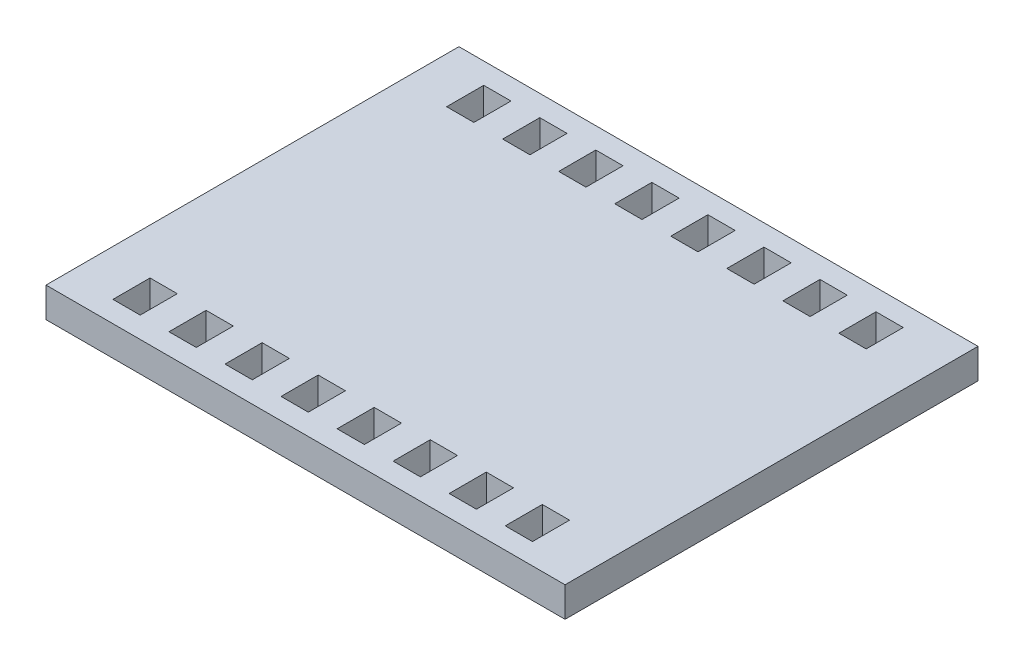
SolidWorks part; units mm, degrees
ref_plane "Front Plane" through (0, 0, 0) normal (0, 0, 1) x (1, 0, 0)
ref_plane "Top Plane" through (0, 0, 0) normal (0, 1, 0) x (1, 0, 0)
ref_plane "Right Plane" through (0, 0, 0) normal (1, 0, 0) x (0, 0, -1)
sketch "Sketch1" plane through (0, 0, 0) normal (0, 1, 0) x (1, 0, 0)
  line L0 (113.6667, 269.5) -> (568.3333, 269.5) construction
  line L1 (8.6379, 33.2139) -> (8.6379, 30.0697)
  line L2 (3.8881, 33.2139) -> (6.1977, 33.2139)
  line L3 (3.8881, 33.2139) -> (3.8881, 30.0697)
  line L4 (3.8881, 30.0697) -> (6.1977, 30.0697)
  line L5 (6.1977, 33.2139) -> (6.1977, 30.0697)
  line L6 (0, 35) -> (43.9961, 35)
  line L7 (0, 35) -> (0, 0)
  line L8 (0, 0) -> (43.9961, 0)
  line L9 (43.9961, 35) -> (43.9961, 0)
  line L10 (8.6379, 33.2139) -> (10.9475, 33.2139)
  line L11 (10.9475, 33.2139) -> (10.9475, 30.0697)
  line L12 (8.6379, 30.0697) -> (10.9475, 30.0697)
  line L13 (13.3877, 33.2139) -> (13.3877, 30.0697)
  line L14 (13.3877, 33.2139) -> (15.6973, 33.2139)
  line L15 (15.6973, 33.2139) -> (15.6973, 30.0697)
  line L16 (13.3877, 30.0697) -> (15.6973, 30.0697)
  line L17 (18.1375, 33.2139) -> (18.1375, 30.0697)
  line L18 (18.1375, 33.2139) -> (20.4471, 33.2139)
  line L19 (20.4471, 33.2139) -> (20.4471, 30.0697)
  line L20 (18.1375, 30.0697) -> (20.4471, 30.0697)
  line L21 (22.8873, 33.2139) -> (22.8873, 30.0697)
  line L22 (22.8873, 33.2139) -> (25.1969, 33.2139)
  line L23 (25.1969, 33.2139) -> (25.1969, 30.0697)
  line L24 (22.8873, 30.0697) -> (25.1969, 30.0697)
  line L25 (27.6371, 33.2139) -> (27.6371, 30.0697)
  line L26 (27.6371, 33.2139) -> (29.9467, 33.2139)
  line L27 (29.9467, 33.2139) -> (29.9467, 30.0697)
  line L28 (27.6371, 30.0697) -> (29.9467, 30.0697)
  line L29 (32.3869, 33.2139) -> (32.3869, 30.0697)
  line L30 (32.3869, 33.2139) -> (34.6965, 33.2139)
  line L31 (34.6965, 33.2139) -> (34.6965, 30.0697)
  line L32 (32.3869, 30.0697) -> (34.6965, 30.0697)
  line L33 (37.1367, 33.2139) -> (37.1367, 30.0697)
  line L34 (37.1367, 33.2139) -> (39.4463, 33.2139)
  line L35 (39.4463, 33.2139) -> (39.4463, 30.0697)
  line L36 (37.1367, 30.0697) -> (39.4463, 30.0697)
  line L37 (43.9961, 17.5) -> (0, 17.5) construction
  line L38 (37.1367, 4.9303) -> (39.4463, 4.9303)
  line L39 (39.4463, 1.7861) -> (39.4463, 4.9303)
  line L40 (37.1367, 1.7861) -> (39.4463, 1.7861)
  line L41 (37.1367, 1.7861) -> (37.1367, 4.9303)
  line L42 (32.3869, 4.9303) -> (34.6965, 4.9303)
  line L43 (34.6965, 1.7861) -> (34.6965, 4.9303)
  line L44 (32.3869, 1.7861) -> (34.6965, 1.7861)
  line L45 (32.3869, 1.7861) -> (32.3869, 4.9303)
  line L46 (27.6371, 4.9303) -> (29.9467, 4.9303)
  line L47 (29.9467, 1.7861) -> (29.9467, 4.9303)
  line L48 (27.6371, 1.7861) -> (29.9467, 1.7861)
  line L49 (27.6371, 1.7861) -> (27.6371, 4.9303)
  line L50 (22.8873, 4.9303) -> (25.1969, 4.9303)
  line L51 (25.1969, 1.7861) -> (25.1969, 4.9303)
  line L52 (22.8873, 1.7861) -> (25.1969, 1.7861)
  line L53 (22.8873, 1.7861) -> (22.8873, 4.9303)
  line L54 (18.1375, 4.9303) -> (20.4471, 4.9303)
  line L55 (20.4471, 1.7861) -> (20.4471, 4.9303)
  line L56 (18.1375, 1.7861) -> (20.4471, 1.7861)
  line L57 (18.1375, 1.7861) -> (18.1375, 4.9303)
  line L58 (13.3877, 4.9303) -> (15.6973, 4.9303)
  line L59 (15.6973, 1.7861) -> (15.6973, 4.9303)
  line L60 (13.3877, 1.7861) -> (15.6973, 1.7861)
  line L61 (13.3877, 1.7861) -> (13.3877, 4.9303)
  line L62 (8.6379, 4.9303) -> (10.9475, 4.9303)
  line L63 (10.9475, 1.7861) -> (10.9475, 4.9303)
  line L64 (8.6379, 1.7861) -> (10.9475, 1.7861)
  line L65 (6.1977, 1.7861) -> (6.1977, 4.9303)
  line L66 (3.8881, 4.9303) -> (6.1977, 4.9303)
  line L67 (3.8881, 1.7861) -> (3.8881, 4.9303)
  line L68 (3.8881, 1.7861) -> (6.1977, 1.7861)
  line L69 (8.6379, 1.7861) -> (8.6379, 4.9303)
  dimension "D1" = 3.8881
  dimension "D2" = 30.0697
  dimension "D3" = 35
  dimension "D4" = 43.9961
  dimension "D5" = 3.1442
  dimension "D6" = 2.3095
  dimension "D8" = 2.4403
  dimension "D7" = 8
extrude "Boss-Extrude1" add sketch "Sketch1" along normal blind 2.54
